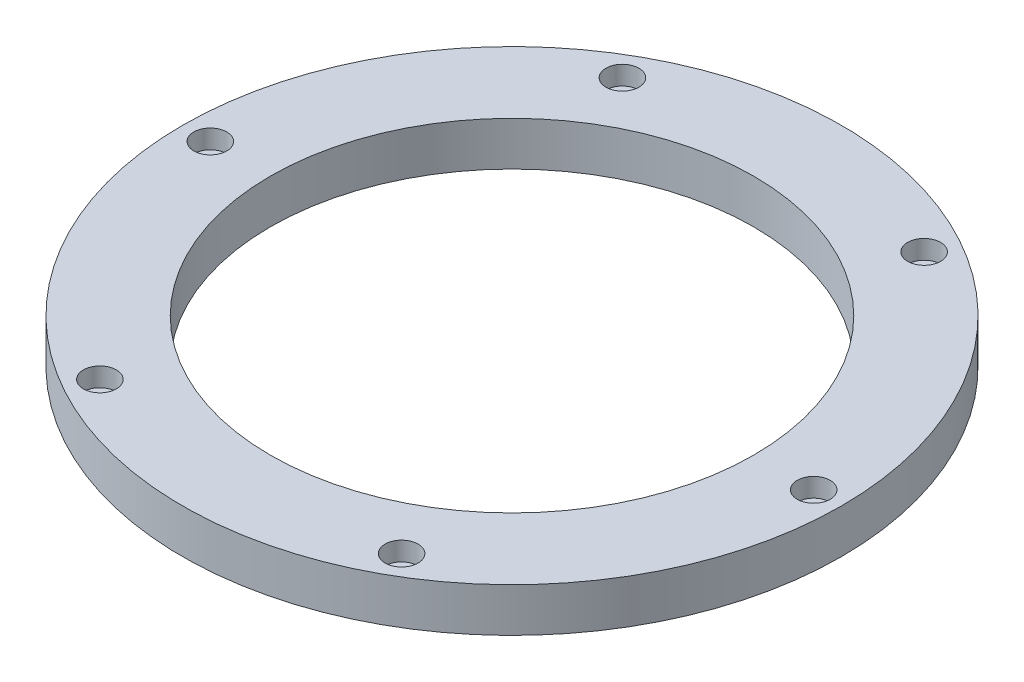
SolidWorks part; units mm, degrees
ref_plane "Płaszczyzna przednia" through (0, 0, 0) normal (0, 0, 1) x (1, 0, 0)
ref_plane "Płaszczyzna górna" through (0, 0, 0) normal (0, 1, 0) x (1, 0, 0)
ref_plane "Płaszczyzna prawa" through (0, 0, 0) normal (1, 0, 0) x (0, 0, -1)
sketch "Szkic1" plane through (0, 0, 0) normal (0, 0, 1) x (1, 0, 0)
  line L0 (0, 8.5311) -> (0, -11.4689) construction
  line L1 (-110, 8.5311) -> (-110, -11.4689)
  line L2 (-150, 8.5311) -> (-150, -11.4689)
  line L3 (-150, 8.5311) -> (-110, 8.5311)
  line L4 (-150, -11.4689) -> (-110, -11.4689)
  dimension "D1" = 110
  dimension "D2" = 20
  dimension "D3" = 150
revolve "Obrót1" add sketch "Szkic1" angle 360 about L0
hole_wizard "Pogłębienie walcowe pod M8 Wkręt z łbem walcowym z gniazdem sześciokątnym1" positions "Szkic2" profile "Szkic3" counterbore size "M8" standard "ISO" end condition through all
sketch "Szkic2" plane through (2.6659, 8.5311, 0) normal (0, 1, 0) x (1, 0, 0)
  point P0 (-139.9824, 0)
  point P1 (-71.3242, 118.9196)
  point P2 (65.9923, 118.9196)
  point P3 (134.6506, 0)
  point P4 (65.9923, -118.9196)
  point P5 (-71.3242, -118.9196)
  point P6 (65.9923, -118.9196)
sketch "Szkic3" plane through (-137.3165, 8.5311, 0) normal (1, 0, 0) x (0, 0, 1)
  line L0 (0, 0) -> (0, 20)
  line L1 (0, 20) -> (4.5, 20)
  line L3 (4.5, 20) -> (4.5, 8.6)
  line L4 (4.5, 8.6) -> (7.5, 8.6)
  line L5 (7.5, 8.6) -> (7.5, 0)
  line L7 (7.5, 0) -> (0, 0)
  line L11 (0, -6.35) -> (0, 107.95) construction
  dimension "Średnica otworu na wylot" = 9
  dimension "Głębokość otworu na wylot" = 20
  dimension "Średnica pogłębienia walcowego" = 15
  dimension "Głębokość pogłębienia walcowego" = 8.6
ref_plane "Płaszczyzna1" through (0, 8.5311, 0) normal (0, 1, 0) x (1, 0, 0)
sketch "Szkic4" plane through (0, 8.5311, 0) normal (0, 1, 0) x (1, 0, 0)
  line L0 (0, 118.9196) -> (0, -118.9196) construction
  line L1 (68.6583, 118.9196) -> (-68.6583, 118.9196)
  line L2 (-68.6583, 118.9196) -> (-137.3165, 0)
  line L3 (-137.3165, 0) -> (-68.6583, -118.9196)
  line L4 (-68.6583, -118.9196) -> (68.6583, -118.9196)
  line L5 (68.6583, -118.9196) -> (137.3165, 0)
  line L6 (137.3165, 0) -> (68.6583, 118.9196)
  circle A0 centre (0, 0) radius 118.9196 construction
  dimension "D1" = 137.3165
